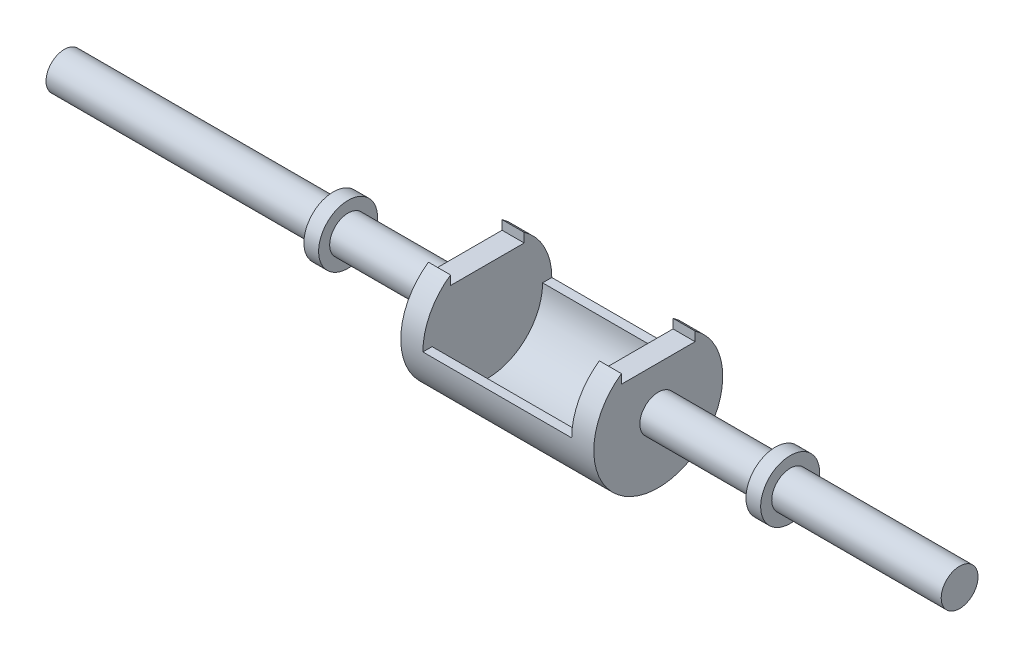
SolidWorks part; units mm, degrees
ref_plane "Front Plane" through (0, 0, 0) normal (0, 0, 1) x (1, 0, 0)
ref_plane "Top Plane" through (0, 0, 0) normal (0, 1, 0) x (1, 0, 0)
ref_plane "Right Plane" through (0, 0, 0) normal (1, 0, 0) x (0, 0, -1)
sketch "Sketch1" plane through (0, 0, 0) normal (0, 0, 1) x (1, 0, 0)
  line L0 (-109.7072, 0) -> (111.0155, 0) construction
  line L1 (-135, 5) -> (-26.2, 5)
  line L2 (-135, 5) -> (-135, 0)
  line L4 (108, 5) -> (108, 0)
  line L5 (0, 36.4132) -> (0, -28.7113) construction
  line L6 (108, 0) -> (20.2, 0)
  line L7 (-26.2, 5) -> (-26.2, 17.5)
  line L8 (-20.2, 15) -> (20.2, 15)
  line L9 (-20.2, 15) -> (-20.2, 0)
  line L11 (20.2, 15) -> (20.2, 0)
  line L12 (-26.2, 17.5) -> (26.2, 17.5)
  line L13 (26.2, 17.5) -> (26.2, 5)
  line L14 (26.2, 5) -> (108, 5)
  line L15 (-20.2, 0) -> (-135, 0)
  dimension "D1" = 108
  dimension "D2" = 5
  dimension "D3" = 15
  dimension "D4" = 135
  dimension "D5" = 40.4
  dimension "D6" = 20.2
  dimension "D7" = 6
  dimension "D8" = 6
  dimension "D9" = 2.5
revolve "Revolve2" add sketch "Sketch1" angle 360 about L0
sketch "Sketch3" plane through (0, 0, 0) normal (0, 0, 1) x (1, 0, 0)
  line L1 (-20.2, 18) -> (20.2, 18)
  line L2 (-20.2, 18) -> (-20.2, 0)
  line L3 (-20.2, 0) -> (20.2, 0)
  line L4 (20.2, 18) -> (20.2, 0)
  dimension "D1" = 40.4
  dimension "D2" = 20.2
  dimension "D3" = 18
extrude "Cut-Extrude1" cut sketch "Sketch3" against normal through all both and the other way through all
sketch "Sketch4" plane through (-26.2, 0, 0) normal (-1, 0, 0) x (0, 0, 1)
  line L5 (-10, 14.3614) -> (-10, 11.8614)
  line L6 (-10, 11.8614) -> (10, 11.8614)
  line L7 (10, 14.3614) -> (10, 11.8614)
  circle A1 centre (0, 0) radius 17.5 construction
  circle A3 centre (0, 0) radius 17.5
  arc A4 (10, 14.3614) -> (-10, 14.3614) centre (0, 0) ccw
  dimension "D1" = 20
  dimension "D2" = 2.5
  dimension "D5" = 2.5
  dimension "D3" = 0
extrude "Cut-Extrude2" cut sketch "Sketch4" against normal up to surface (52.4 mm away) up to face at (26.2, 0, 17.5)
ref_plane "Plane1" through (60, 0, 0) normal (1, 0, 0) x (0, 0, -1)
ref_plane "Plane2" through (-60, 0, 0) normal (1, 0, 0) x (0, 0, -1)
sketch "Sketch5" plane through (60, 0, 0) normal (1, 0, 0) x (0, 0, -1)
  circle A0 centre (0, 0) radius 8
  dimension "D1" = 16
extrude "Boss-Extrude1" add sketch "Sketch5" along normal blind 2 and the other way blind 2
sketch "Sketch6" plane through (-60, 0, 0) normal (1, 0, 0) x (0, 0, -1)
  circle A1 centre (0, 0) radius 8
  circle A2 centre (0, 0) radius 8
  dimension "D1" = 0
extrude "Boss-Extrude2" add sketch "Sketch6" along normal blind 2 and the other way blind 2
